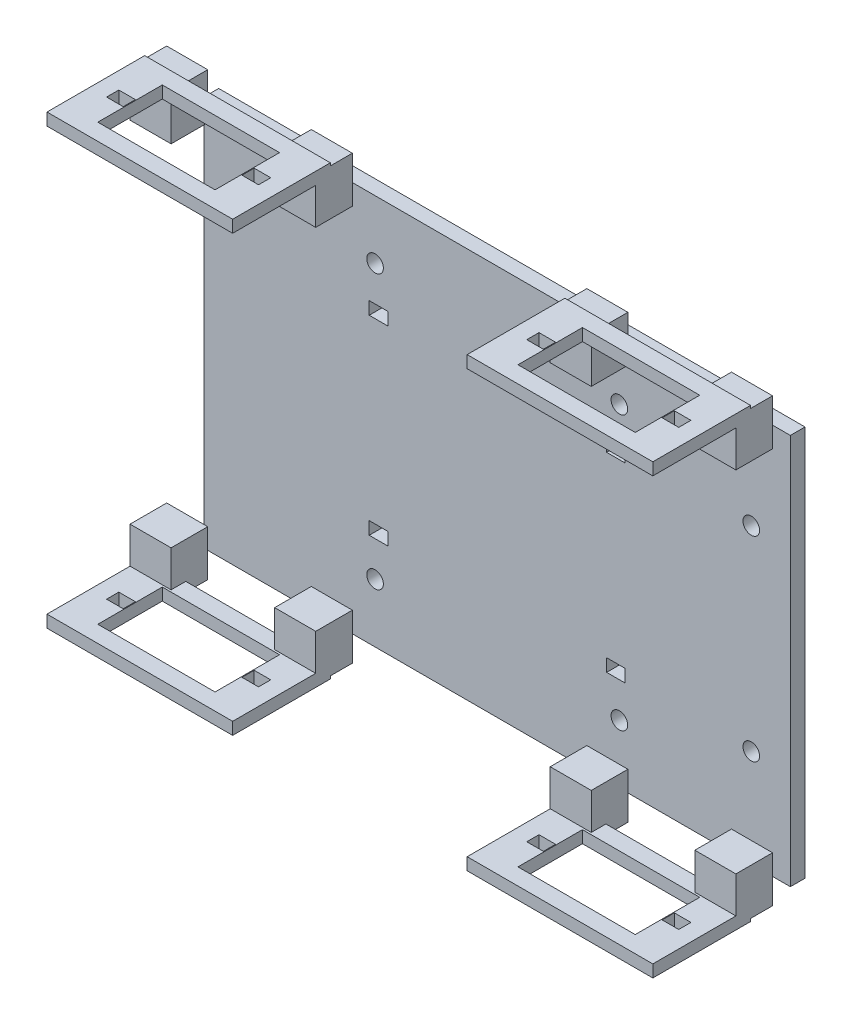
SolidWorks part; units mm, degrees
ref_plane "前视基准面" through (0, 0, 0) normal (0, 0, 1) x (1, 0, 0)
ref_plane "上视基准面" through (0, 0, 0) normal (0, 1, 0) x (1, 0, 0)
ref_plane "右视基准面" through (0, 0, 0) normal (1, 0, 0) x (0, 0, -1)
other "Configuration Table"
sketch "草图1" plane through (0, 0, 0) normal (0, 0, 1) x (1, 0, 0)
  line L0 (-60, -40) -> (60, -40)
  line L1 (60, -40) -> (60, 40)
  line L2 (60, 40) -> (-60, 40)
  line L3 (-60, 40) -> (-60, -40)
extrude "Deck_120x80x3" add sketch "草图1" along normal blind 3 from offset 0
sketch "草图2" plane through (0, 0, 0) normal (0, 0, 1) x (1, 0, 0)
  line L0 (-67.65, -45.2) -> (-59.25, -45.2)
  line L1 (-59.25, -45.2) -> (-59.25, -35.8)
  line L2 (-59.25, -35.8) -> (-67.65, -35.8)
  line L3 (-67.65, -35.8) -> (-67.65, -45.2)
extrude "Frame_rib" add sketch "草图2" along normal blind 7.5 from offset 3
sketch "草图3" plane through (0, 0, 0) normal (0, 0, 1) x (1, 0, 0)
  line L0 (-38.05, -45.2) -> (-29.65, -45.2)
  line L1 (-29.65, -45.2) -> (-29.65, -35.8)
  line L2 (-29.65, -35.8) -> (-38.05, -35.8)
  line L3 (-38.05, -35.8) -> (-38.05, -45.2)
extrude "凸台-拉伸3" add sketch "草图3" along normal blind 7.5 from offset 3
sketch "草图4" plane through (0, 0, 0) normal (0, 0, 1) x (1, 0, 0)
  line L0 (-67.65, -45.75) -> (-60.65, -45.75)
  line L1 (-60.65, -45.75) -> (-60.65, -43.25)
  line L2 (-60.65, -43.25) -> (-67.65, -43.25)
  line L3 (-67.65, -43.25) -> (-67.65, -45.75)
extrude "Mount_upright" add sketch "草图4" along normal blind 17 from offset 10.5
sketch "草图5" plane through (0, 0, 0) normal (0, 0, 1) x (1, 0, 0)
  line L0 (-36.65, -45.75) -> (-29.65, -45.75)
  line L1 (-29.65, -45.75) -> (-29.65, -43.25)
  line L2 (-29.65, -43.25) -> (-36.65, -43.25)
  line L3 (-36.65, -43.25) -> (-36.65, -45.75)
extrude "凸台-拉伸5" add sketch "草图5" along normal blind 17 from offset 10.5
sketch "草图6" plane through (0, 0, 0) normal (0, 0, 1) x (1, 0, 0)
  line L0 (-67.65, -45.75) -> (-29.65, -45.75)
  line L1 (-29.65, -45.75) -> (-29.65, -43.25)
  line L2 (-29.65, -43.25) -> (-67.65, -43.25)
  line L3 (-67.65, -43.25) -> (-67.65, -45.75)
extrude "Mount_lower_beam" add sketch "草图6" along normal blind 3.4 from offset 7.5
sketch "草图7" plane through (0, 0, 0) normal (0, 0, 1) x (1, 0, 0)
  line L0 (-67.65, -45.75) -> (-29.65, -45.75)
  line L1 (-29.65, -45.75) -> (-29.65, -43.25)
  line L2 (-29.65, -43.25) -> (-67.65, -43.25)
  line L3 (-67.65, -43.25) -> (-67.65, -45.75)
extrude "Mount_upper_beam" add sketch "草图7" along normal blind 3.4 from offset 24.1
sketch "草图8" plane through (0, 0, 0) normal (0, 1, 0) x (1, 0, 0)
  line L0 (-64.2, -16.25) -> (-60.8, -16.25)
  line L1 (-60.8, -16.25) -> (-60.8, -18.75)
  line L2 (-60.8, -18.75) -> (-64.2, -18.75)
  line L3 (-64.2, -18.75) -> (-64.2, -16.25)
  line L4 (-36.5, -16.25) -> (-33.1, -16.25)
  line L5 (-33.1, -16.25) -> (-33.1, -18.75)
  line L6 (-33.1, -18.75) -> (-36.5, -18.75)
  line L7 (-36.5, -18.75) -> (-36.5, -16.25)
extrude "Servo_ear_adjustable_slots" cut sketch "草图8" along normal blind 4 from offset 46.5
sketch "草图9" plane through (0, 0, 0) normal (0, 0, 1) x (1, 0, 0)
  line L0 (-67.65, 35.8) -> (-59.25, 35.8)
  line L1 (-59.25, 35.8) -> (-59.25, 45.2)
  line L2 (-59.25, 45.2) -> (-67.65, 45.2)
  line L3 (-67.65, 45.2) -> (-67.65, 35.8)
extrude "凸台-拉伸8" add sketch "草图9" along normal blind 7.5 from offset 3
sketch "草图10" plane through (0, 0, 0) normal (0, 0, 1) x (1, 0, 0)
  line L0 (-38.05, 35.8) -> (-29.65, 35.8)
  line L1 (-29.65, 35.8) -> (-29.65, 45.2)
  line L2 (-29.65, 45.2) -> (-38.05, 45.2)
  line L3 (-38.05, 45.2) -> (-38.05, 35.8)
extrude "凸台-拉伸9" add sketch "草图10" along normal blind 7.5 from offset 3
sketch "草图11" plane through (0, 0, 0) normal (0, 0, 1) x (1, 0, 0)
  line L0 (-67.65, 43.25) -> (-60.65, 43.25)
  line L1 (-60.65, 43.25) -> (-60.65, 45.75)
  line L2 (-60.65, 45.75) -> (-67.65, 45.75)
  line L3 (-67.65, 45.75) -> (-67.65, 43.25)
extrude "凸台-拉伸10" add sketch "草图11" along normal blind 17 from offset 10.5
sketch "草图12" plane through (0, 0, 0) normal (0, 0, 1) x (1, 0, 0)
  line L0 (-36.65, 43.25) -> (-29.65, 43.25)
  line L1 (-29.65, 43.25) -> (-29.65, 45.75)
  line L2 (-29.65, 45.75) -> (-36.65, 45.75)
  line L3 (-36.65, 45.75) -> (-36.65, 43.25)
extrude "凸台-拉伸11" add sketch "草图12" along normal blind 17 from offset 10.5
sketch "草图13" plane through (0, 0, 0) normal (0, 0, 1) x (1, 0, 0)
  line L0 (-67.65, 43.25) -> (-29.65, 43.25)
  line L1 (-29.65, 43.25) -> (-29.65, 45.75)
  line L2 (-29.65, 45.75) -> (-67.65, 45.75)
  line L3 (-67.65, 45.75) -> (-67.65, 43.25)
extrude "凸台-拉伸12" add sketch "草图13" along normal blind 3.4 from offset 7.5
sketch "草图14" plane through (0, 0, 0) normal (0, 0, 1) x (1, 0, 0)
  line L0 (-67.65, 43.25) -> (-29.65, 43.25)
  line L1 (-29.65, 43.25) -> (-29.65, 45.75)
  line L2 (-29.65, 45.75) -> (-67.65, 45.75)
  line L3 (-67.65, 45.75) -> (-67.65, 43.25)
extrude "凸台-拉伸13" add sketch "草图14" along normal blind 3.4 from offset 24.1
sketch "草图15" plane through (0, 0, 0) normal (0, 1, 0) x (1, 0, 0)
  line L0 (-64.2, -16.25) -> (-60.8, -16.25)
  line L1 (-60.8, -16.25) -> (-60.8, -18.75)
  line L2 (-60.8, -18.75) -> (-64.2, -18.75)
  line L3 (-64.2, -18.75) -> (-64.2, -16.25)
  line L4 (-36.5, -16.25) -> (-33.1, -16.25)
  line L5 (-33.1, -16.25) -> (-33.1, -18.75)
  line L6 (-33.1, -18.75) -> (-36.5, -18.75)
  line L7 (-36.5, -18.75) -> (-36.5, -16.25)
extrude "切除-拉伸2" cut sketch "草图15" along normal blind 4 from offset 42.5
sketch "草图16" plane through (0, 0, 0) normal (0, 0, 1) x (1, 0, 0)
  line L0 (18.35, -45.2) -> (26.75, -45.2)
  line L1 (26.75, -45.2) -> (26.75, -35.8)
  line L2 (26.75, -35.8) -> (18.35, -35.8)
  line L3 (18.35, -35.8) -> (18.35, -45.2)
extrude "凸台-拉伸14" add sketch "草图16" along normal blind 7.5 from offset 3
sketch "草图17" plane through (0, 0, 0) normal (0, 0, 1) x (1, 0, 0)
  line L0 (47.95, -45.2) -> (56.35, -45.2)
  line L1 (56.35, -45.2) -> (56.35, -35.8)
  line L2 (56.35, -35.8) -> (47.95, -35.8)
  line L3 (47.95, -35.8) -> (47.95, -45.2)
extrude "凸台-拉伸15" add sketch "草图17" along normal blind 7.5 from offset 3
sketch "草图18" plane through (0, 0, 0) normal (0, 0, 1) x (1, 0, 0)
  line L0 (18.35, -45.75) -> (25.35, -45.75)
  line L1 (25.35, -45.75) -> (25.35, -43.25)
  line L2 (25.35, -43.25) -> (18.35, -43.25)
  line L3 (18.35, -43.25) -> (18.35, -45.75)
extrude "凸台-拉伸16" add sketch "草图18" along normal blind 17 from offset 10.5
sketch "草图19" plane through (0, 0, 0) normal (0, 0, 1) x (1, 0, 0)
  line L0 (49.35, -45.75) -> (56.35, -45.75)
  line L1 (56.35, -45.75) -> (56.35, -43.25)
  line L2 (56.35, -43.25) -> (49.35, -43.25)
  line L3 (49.35, -43.25) -> (49.35, -45.75)
extrude "凸台-拉伸17" add sketch "草图19" along normal blind 17 from offset 10.5
sketch "草图20" plane through (0, 0, 0) normal (0, 0, 1) x (1, 0, 0)
  line L0 (18.35, -45.75) -> (56.35, -45.75)
  line L1 (56.35, -45.75) -> (56.35, -43.25)
  line L2 (56.35, -43.25) -> (18.35, -43.25)
  line L3 (18.35, -43.25) -> (18.35, -45.75)
extrude "凸台-拉伸18" add sketch "草图20" along normal blind 3.4 from offset 7.5
sketch "草图21" plane through (0, 0, 0) normal (0, 0, 1) x (1, 0, 0)
  line L0 (18.35, -45.75) -> (56.35, -45.75)
  line L1 (56.35, -45.75) -> (56.35, -43.25)
  line L2 (56.35, -43.25) -> (18.35, -43.25)
  line L3 (18.35, -43.25) -> (18.35, -45.75)
extrude "凸台-拉伸19" add sketch "草图21" along normal blind 3.4 from offset 24.1
sketch "草图22" plane through (0, 0, 0) normal (0, 1, 0) x (1, 0, 0)
  line L0 (21.8, -16.25) -> (25.2, -16.25)
  line L1 (25.2, -16.25) -> (25.2, -18.75)
  line L2 (25.2, -18.75) -> (21.8, -18.75)
  line L3 (21.8, -18.75) -> (21.8, -16.25)
  line L4 (49.5, -16.25) -> (52.9, -16.25)
  line L5 (52.9, -16.25) -> (52.9, -18.75)
  line L6 (52.9, -18.75) -> (49.5, -18.75)
  line L7 (49.5, -18.75) -> (49.5, -16.25)
extrude "切除-拉伸3" cut sketch "草图22" along normal blind 4 from offset 46.5
sketch "草图23" plane through (0, 0, 0) normal (0, 0, 1) x (1, 0, 0)
  line L0 (18.35, 35.8) -> (26.75, 35.8)
  line L1 (26.75, 35.8) -> (26.75, 45.2)
  line L2 (26.75, 45.2) -> (18.35, 45.2)
  line L3 (18.35, 45.2) -> (18.35, 35.8)
extrude "凸台-拉伸20" add sketch "草图23" along normal blind 7.5 from offset 3
sketch "草图24" plane through (0, 0, 0) normal (0, 0, 1) x (1, 0, 0)
  line L0 (47.95, 35.8) -> (56.35, 35.8)
  line L1 (56.35, 35.8) -> (56.35, 45.2)
  line L2 (56.35, 45.2) -> (47.95, 45.2)
  line L3 (47.95, 45.2) -> (47.95, 35.8)
extrude "凸台-拉伸21" add sketch "草图24" along normal blind 7.5 from offset 3
sketch "草图25" plane through (0, 0, 0) normal (0, 0, 1) x (1, 0, 0)
  line L0 (18.35, 43.25) -> (25.35, 43.25)
  line L1 (25.35, 43.25) -> (25.35, 45.75)
  line L2 (25.35, 45.75) -> (18.35, 45.75)
  line L3 (18.35, 45.75) -> (18.35, 43.25)
extrude "凸台-拉伸22" add sketch "草图25" along normal blind 17 from offset 10.5
sketch "草图26" plane through (0, 0, 0) normal (0, 0, 1) x (1, 0, 0)
  line L0 (49.35, 43.25) -> (56.35, 43.25)
  line L1 (56.35, 43.25) -> (56.35, 45.75)
  line L2 (56.35, 45.75) -> (49.35, 45.75)
  line L3 (49.35, 45.75) -> (49.35, 43.25)
extrude "凸台-拉伸23" add sketch "草图26" along normal blind 17 from offset 10.5
sketch "草图27" plane through (0, 0, 0) normal (0, 0, 1) x (1, 0, 0)
  line L0 (18.35, 43.25) -> (56.35, 43.25)
  line L1 (56.35, 43.25) -> (56.35, 45.75)
  line L2 (56.35, 45.75) -> (18.35, 45.75)
  line L3 (18.35, 45.75) -> (18.35, 43.25)
extrude "凸台-拉伸24" add sketch "草图27" along normal blind 3.4 from offset 7.5
sketch "草图28" plane through (0, 0, 0) normal (0, 0, 1) x (1, 0, 0)
  line L0 (18.35, 43.25) -> (56.35, 43.25)
  line L1 (56.35, 43.25) -> (56.35, 45.75)
  line L2 (56.35, 45.75) -> (18.35, 45.75)
  line L3 (18.35, 45.75) -> (18.35, 43.25)
extrude "凸台-拉伸25" add sketch "草图28" along normal blind 3.4 from offset 24.1
sketch "草图29" plane through (0, 0, 0) normal (0, 1, 0) x (1, 0, 0)
  line L0 (21.8, -16.25) -> (25.2, -16.25)
  line L1 (25.2, -16.25) -> (25.2, -18.75)
  line L2 (25.2, -18.75) -> (21.8, -18.75)
  line L3 (21.8, -18.75) -> (21.8, -16.25)
  line L4 (49.5, -16.25) -> (52.9, -16.25)
  line L5 (52.9, -16.25) -> (52.9, -18.75)
  line L6 (52.9, -18.75) -> (49.5, -18.75)
  line L7 (49.5, -18.75) -> (49.5, -16.25)
extrude "切除-拉伸4" cut sketch "草图29" along normal blind 4 from offset 42.5
sketch "草图30" plane through (0, 0, 0) normal (0, 0, 1) x (1, 0, 0)
  circle A0 centre (-25, -28) radius 1.7
  circle A1 centre (-25, 28) radius 1.7
  circle A2 centre (25, -28) radius 1.7
  circle A3 centre (25, 28) radius 1.7
  circle A4 centre (52, -20) radius 1.7
  circle A5 centre (52, 20) radius 1.7
extrude "M3_deck_mounting_holes" cut sketch "草图30" along normal blind 3.2 from offset 0.1
sketch "草图31" plane through (0, 0, 0) normal (0, 0, 1) x (1, 0, 0)
  line L0 (-26.2, -20.8) -> (-22.4, -20.8)
  line L1 (-22.4, -20.8) -> (-22.4, -18.2)
  line L2 (-22.4, -18.2) -> (-26.2, -18.2)
  line L3 (-26.2, -18.2) -> (-26.2, -20.8)
  line L4 (-26.2, 18.2) -> (-22.4, 18.2)
  line L5 (-22.4, 18.2) -> (-22.4, 20.8)
  line L6 (-22.4, 20.8) -> (-26.2, 20.8)
  line L7 (-26.2, 20.8) -> (-26.2, 18.2)
  line L8 (22.4, -20.8) -> (26.2, -20.8)
  line L9 (26.2, -20.8) -> (26.2, -18.2)
  line L10 (26.2, -18.2) -> (22.4, -18.2)
  line L11 (22.4, -18.2) -> (22.4, -20.8)
  line L12 (22.4, 18.2) -> (26.2, 18.2)
  line L13 (26.2, 18.2) -> (26.2, 20.8)
  line L14 (26.2, 20.8) -> (22.4, 20.8)
  line L15 (22.4, 20.8) -> (22.4, 18.2)
extrude "PCB_screw_access" cut sketch "草图31" along normal blind 3.2 from offset 0.1
